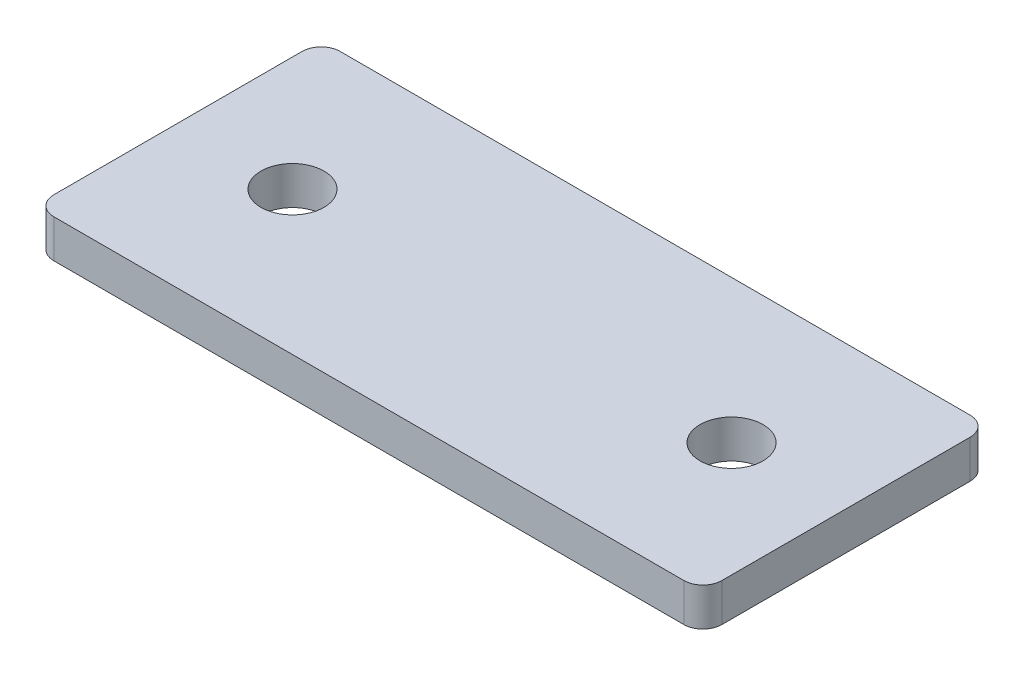
SolidWorks part; units mm, degrees
ref_plane "Front Plane" through (0, 0, 0) normal (0, 0, 1) x (1, 0, 0)
ref_plane "Top Plane" through (0, 0, 0) normal (0, 1, 0) x (1, 0, 0)
ref_plane "Right Plane" through (0, 0, 0) normal (1, 0, 0) x (0, 0, -1)
sketch "Sketch1" plane through (0, 0, 0) normal (0, 1, 0) x (1, 0, 0)
  line L1 (35, -15) -> (-35, -15)
  line L2 (35, -15) -> (35, 15)
  line L3 (35, 15) -> (-35, 15)
  line L4 (-35, -15) -> (-35, 15)
  line L5 (35, -15) -> (-35, 15) construction
  line L6 (35, 15) -> (-35, -15) construction
  line L8 (0, -55) -> (0, 55) construction
  point P5 (0, 0)
  dimension "D7" = 70
  dimension "D8" = 30
extrude "Boss-Extrude1" add sketch "Sketch1" along normal blind 4
fillet "Fillet1" radius 2 4 edges at (35, 2, 15) (35, 2, -15) (-35, 2, -15) (-35, 2, 15)
hole_wizard "M6 Clearance Hole1" positions "Sketch3" profile "Sketch2" hole size "M6" standard "ISO"
sketch "Sketch3" plane through (0, 4, 0) normal (0, 1, 0) x (1, 0, 0)
  line L0 (-42.2687, 0) -> (56.8217, 0) construction
  line L1 (-2.2, 0) -> (2.2, 0) construction
  line L3 (0, 18.8846) -> (0, -31.0081) construction
  line L4 (0, -2.2) -> (0, 2.2) construction
  point P0 (-23, 0)
  point P25 (23, 0)
  dimension "D2" = 23
sketch "Sketch2" plane through (-23, 4, 0) normal (1, 0, 0) x (0, 0, 1)
  line L0 (0, 0) -> (0, 8.9828)
  line L1 (0, 8.9828) -> (3.3, 7)
  line L2 (3.3, 7) -> (3.3, 0)
  line L5 (3.3, 0) -> (0, 0)
  line L10 (0, 8.9828) -> (-3.3, 7) construction
  line L11 (0, -6.35) -> (0, 107.95) construction
  dimension "Hole Dia." = 6.6
  dimension "Hole Depth" = 7
  dimension "Drill Angle" = 118
